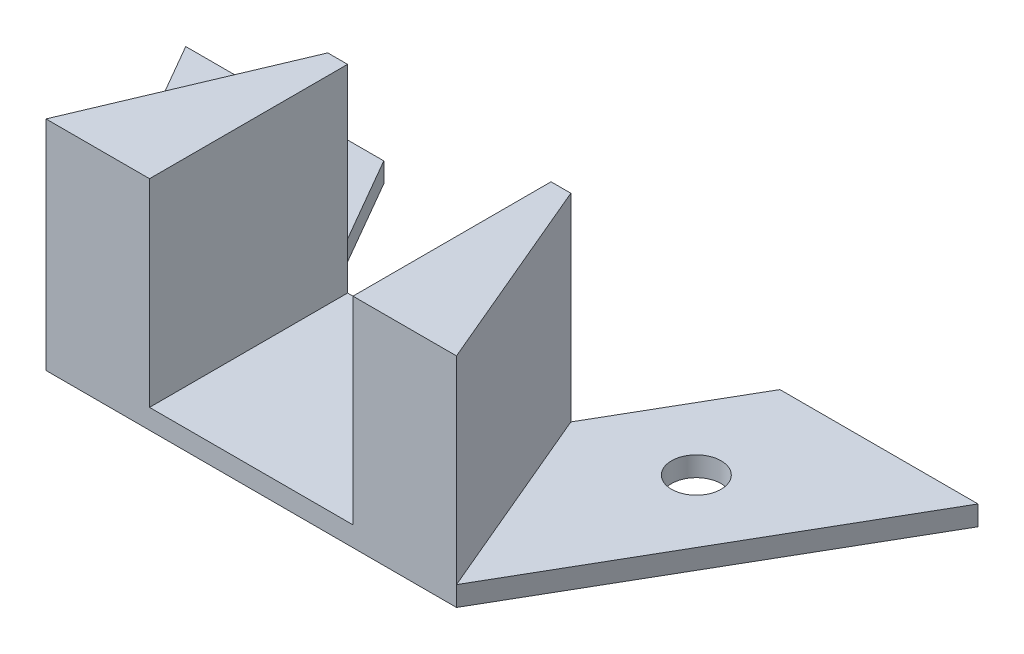
SolidWorks part; units mm, degrees
ref_plane "Front Plane" through (0, 0, 0) normal (0, 0, 1) x (1, 0, 0)
ref_plane "Top Plane" through (0, 0, 0) normal (0, 1, 0) x (1, 0, 0)
ref_plane "Right Plane" through (0, 0, 0) normal (1, 0, 0) x (0, 0, -1)
sketch "Sketch1" plane through (0, 0, 0) normal (0, 1, 0) x (1, 0, 0)
  line L0 (25.4, 0) -> (-25.4, 0)
  line L1 (-25.4, 0) -> (-50.8, 0)
  line L2 (-25.4, 0) -> (-15.585, -17)
  line L3 (-15.585, -17) -> (15.585, -17)
  line L4 (15.585, -17) -> (25.4, 0)
  line L5 (25.4, 0) -> (50.8, 0)
  line L6 (50.8, 0) -> (26.3203, -42.4)
  line L7 (26.3203, -42.4) -> (-26.3203, -42.4)
  line L8 (-23.3776, 23.4911) -> (-36.0776, 1.4941) [skipped]
  line L9 (0, 36.9882) -> (-25.4, 36.9882) [skipped]
  line L10 (23.3776, 23.4911) -> (10.6776, 45.4882) [skipped]
  line L11 (-26.3203, -42.4) -> (-50.8, 0)
  point P4 (0, 0)
  dimension "D1" = 50.8
  dimension "D2" = 17
  dimension "D3" = 25.4
  dimension "D4" = 48.9593
  dimension "D6" = 60
  dimension "D7" = 60
  dimension "D8" = 25.4
  dimension "D9" = 25.4
  dimension "D10" = 120
  dimension "D11" = 120
extrude "Boss-Extrude1" add sketch "Sketch1" along normal blind 2.54 contours L11 L7 L6 L5 L4 L3 L2 L1
sketch "Sketch2" plane through (0, 2.54, 0) normal (0, 1, 0) x (1, 0, 0)
  line L0 (-26.3203, -42.4) -> (-15.585, -17)
  line L1 (-13.045, -17) -> (-13.045, -42.4)
  line L2 (15.585, -17) -> (26.3203, -42.4)
  line L3 (-15.585, -17) -> (15.585, -17) construction
  line L4 (26.3203, -42.4) -> (-26.3203, -42.4) construction
  line L5 (13.045, -17) -> (13.045, -42.4)
  line L6 (13.045, -42.4) -> (26.3203, -42.4)
  line L7 (15.585, -17) -> (13.045, -17)
  line L8 (-13.045, -17) -> (-15.585, -17)
  line L9 (-13.045, -42.4) -> (-26.3203, -42.4)
  dimension "D1" = 2.54
  dimension "D2" = 2.54
  dimension "D3" = 26.0901
extrude "Boss-Extrude2" add sketch "Sketch2" along normal blind 25.4
sketch "Sketch3" plane through (0, 2.54, 0) normal (0, 1, 0) x (1, 0, 0)
  line L0 (-38.5602, -21.2) -> (-20.4925, -8.5) construction
  line L3 (-26.3203, -42.4) -> (-50.8, 0) construction
  line L4 (-25.4, 0) -> (-15.585, -17) construction
  line L5 (20.4925, -8.5) -> (38.5602, -21.2) construction
  line L6 (15.585, -17) -> (25.4, 0) construction
  line L7 (50.8, 0) -> (26.3203, -42.4) construction
  point P20 (-29.5263, -14.85)
  point P21 (29.5263, -14.85)
hole_wizard "1/4 (0.25) Diameter Hole1" positions "3DSketch1" profile "Sketch4" hole size "1/4" standard "ANSI Inch" end condition through all
sketch3d "3DSketch1"
  point P0 (29.5263, 2.54, 14.85)
  point P3 (-29.5263, 2.54, 14.85)
sketch "Sketch4" plane through (29.5263, 2.54, 14.85) normal (1, 0, 0) x (0, 0, 1)
  line L0 (0, 0) -> (0, 2.54)
  line L1 (0, 2.54) -> (3.175, 2.54)
  line L2 (3.175, 2.54) -> (3.175, 0)
  line L5 (3.175, 0) -> (0, 0)
  line L11 (0, -6.35) -> (0, 107.95) construction
  dimension "Thru Hole Dia." = 6.35
  dimension "Thru Hole Depth" = 2.54
